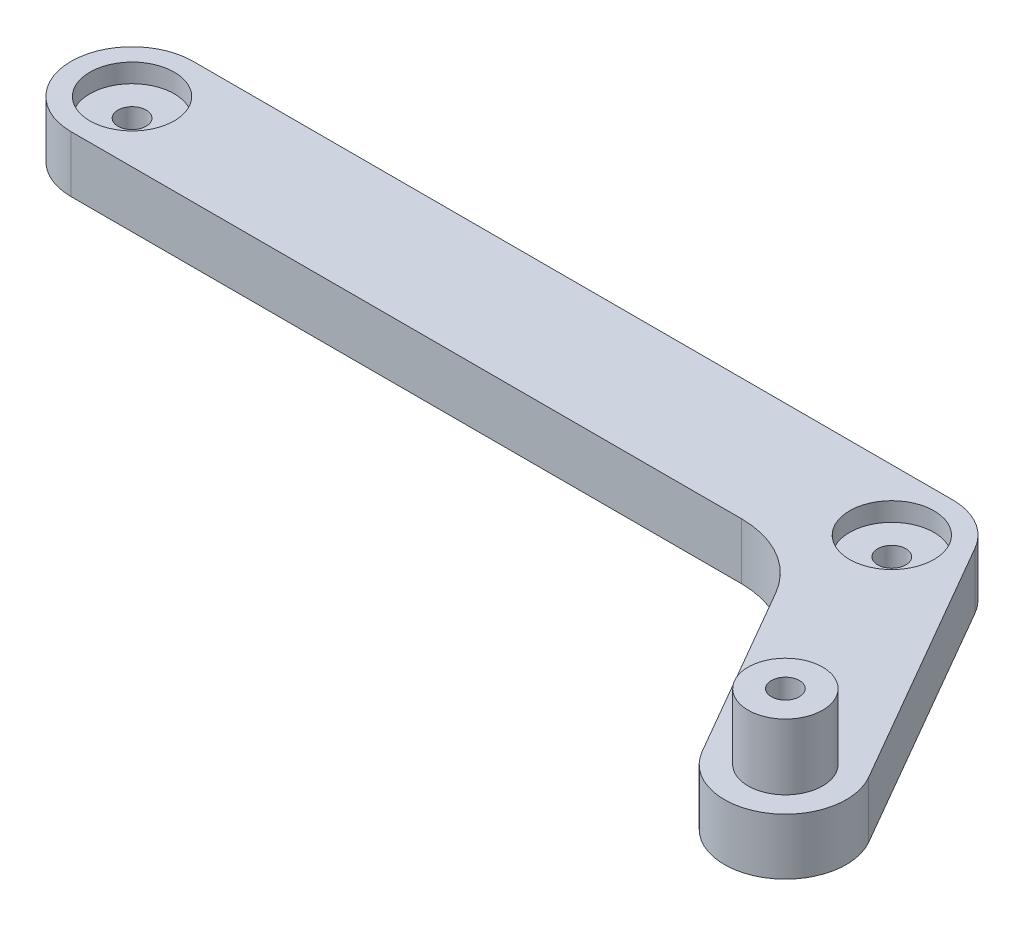
SolidWorks part; units mm, degrees
ref_plane "Front Plane" through (0, 0, 0) normal (0, 0, 1) x (1, 0, 0)
ref_plane "Top Plane" through (0, 0, 0) normal (0, 1, 0) x (1, 0, 0)
ref_plane "Right Plane" through (0, 0, 0) normal (1, 0, 0) x (0, 0, -1)
sketch "Sketch1" plane through (0, 0, 0) normal (0, 1, 0) x (1, 0, 0)
  line L0 (0, 0) -> (81, 0) construction
  line L1 (0, 6.5) -> (81, 6.5)
  line L2 (0, -6.5) -> (71.4737, -6.5)
  line L3 (81, 0) -> (96.5, -26.8468) construction
  line L4 (80.134, -11.5) -> (90.8708, -30.0968)
  line L5 (86.6292, 3.25) -> (102.1292, -23.5968)
  line L6 (75.3708, -3.25) -> (90.8708, -30.0968) construction
  circle A0 centre (0, 0) radius 1.5
  arc A1 (0, 6.5) -> (0, -6.5) centre (0, 0) ccw
  circle A3 centre (81, 0) radius 1.5
  circle A4 centre (0, 0) radius 6.5 construction
  circle A5 centre (96.5, -26.8468) radius 1.5
  arc A9 (81.4913, -6.4814) -> (85.8238, -4.3567) centre (81, 0) ccw [skipped]
  arc A10 (81, 6.5) -> (84.25, -5.6292) centre (81, 0) ccw construction
  circle A11 centre (81, 0) radius 6.5 construction
  arc A12 (90.8708, -30.0968) -> (102.1292, -23.5968) centre (96.5, -26.8468) ccw
  arc A13 (86.6292, 3.25) -> (81, 6.5) centre (81, 0) ccw
  arc A14 (80.134, -11.5) -> (71.4737, -6.5) centre (71.4737, -16.5) ccw
  circle A15 centre (96.5, -26.8468) radius 6.5 construction
  dimension "D1" = 3
  dimension "D5" = 3
  dimension "D7" = 10
  dimension "D4" = 81
  dimension "D8" = 31
  dimension "D6" = 120
  dimension "D2" = 5
  dimension "D11" = 6.5
  dimension "D3" = 2
extrude "Boss-Extrude1" add sketch "Sketch1" along normal blind 6
sketch "Sketch2" plane through (0, 6, 0) normal (0, 1, 0) x (1, 0, 0)
  circle A5 centre (0, 0) radius 4.5
  circle A6 centre (0, 0) radius 4.5
  circle A8 centre (81, 0) radius 4.5
  circle A9 centre (81, 0) radius 4.5
  dimension "D1" = 3
  dimension "D2" = 3
extrude "Cut-Extrude1" cut sketch "Sketch2" against normal blind 2
sketch "Sketch3" plane through (0, 6, 0) normal (0, 1, 0) x (1, 0, 0)
  circle A0 centre (96.5, -26.8468) radius 3.975
  circle A1 centre (96.5, -26.8468) radius 1.5 construction
  arc A2 (90.8708, -30.0968) -> (102.1292, -23.5968) centre (96.5, -26.8468) ccw construction
  circle A3 centre (96.5, -26.8468) radius 1.5
  dimension "D1" = 7.95
extrude "Boss-Extrude2" add sketch "Sketch3" along normal blind 7
